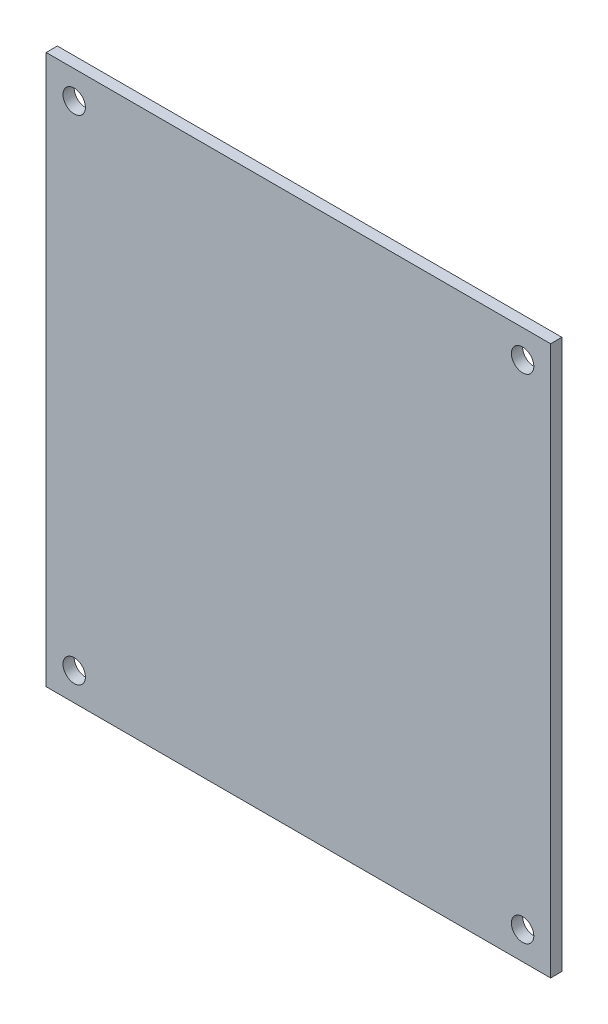
SolidWorks part; units mm, degrees
material "Acrylic (Medium-high impact)"
ref_plane "Front Plane" through (0, 0, 0) normal (0, 0, 1) x (1, 0, 0)
ref_plane "Top Plane" through (0, 0, 0) normal (0, 1, 0) x (1, 0, 0)
ref_plane "Right Plane" through (0, 0, 0) normal (1, 0, 0) x (0, 0, -1)
sketch "Sketch1" plane through (0, 0, 0) normal (0, 0, 1) x (1, 0, 0)
  line L0 (-67.5, 73.5) -> (67.5, 73.5)
  line L1 (-67.5, 73.5) -> (-67.5, -73.5)
  line L2 (-67.5, -73.5) -> (67.5, -73.5)
  line L3 (67.5, 73.5) -> (67.5, -73.5)
  dimension "D1" = 147
  dimension "D2" = 135
  dimension "D3" = 73.5
  dimension "D4" = 67.5
extrude "Boss-Extrude1" add sketch "Sketch1" along normal blind 3
sketch "Sketch2" plane through (0, 0, 3) normal (0, 0, 1) x (1, 0, 0)
  line L0 (67.5, 73.5) -> (60, 73.5) construction
  line L2 (60, 66) -> (60, 73.5) construction
  line L3 (-60, 66) -> (-60, 73.5) construction
  line L4 (67.5, 73.5) -> (-67.5, 73.5) construction
  line L5 (-60, 73.5) -> (-67.5, 73.5) construction
  line L6 (-60, -66) -> (-67.5, -66) construction
  line L7 (-67.5, 73.5) -> (-67.5, -73.5) construction
  line L8 (-67.5, -66) -> (-67.5, -73.5) construction
  line L9 (60, -66) -> (67.5, -66) construction
  line L10 (67.5, -73.5) -> (67.5, 73.5) construction
  line L11 (67.5, -66) -> (67.5, -73.5) construction
  point P3 (-60, 66)
  point P5 (60, 66)
  point P7 (60, -66)
  point P8 (-60, -66)
  dimension "D1" = 7.5
  dimension "D2" = 7.5
  dimension "D3" = 7.5
  dimension "D4" = 7.5
  dimension "D5" = 7.5
  dimension "D6" = 7.5
  dimension "D7" = 7.5
  dimension "D8" = 7.5
hole_wizard "Ø6.0 (6) Diameter Hole1" positions "Sketch3" profile "Sketch4" hole size "Ø6.0" standard "AS" end condition through all
sketch "Sketch3" plane through (0, 0, 3) normal (0, 0, 1) x (1, 0, 0)
  point P0 (60, -66)
  point P3 (-60, -66)
  point P6 (-60, 66)
  point P9 (60, 66)
sketch "Sketch4" plane through (60, -66, 3) normal (1, 0, 0) x (0, -1, 0)
  line L0 (0, 0) -> (0, 3)
  line L1 (0, 3) -> (3, 3)
  line L2 (3, 3) -> (3, 0)
  line L5 (3, 0) -> (0, 0)
  line L11 (0, -6.35) -> (0, 107.95) construction
  dimension "Thru Hole Dia." = 6
  dimension "Thru Hole Depth" = 3
